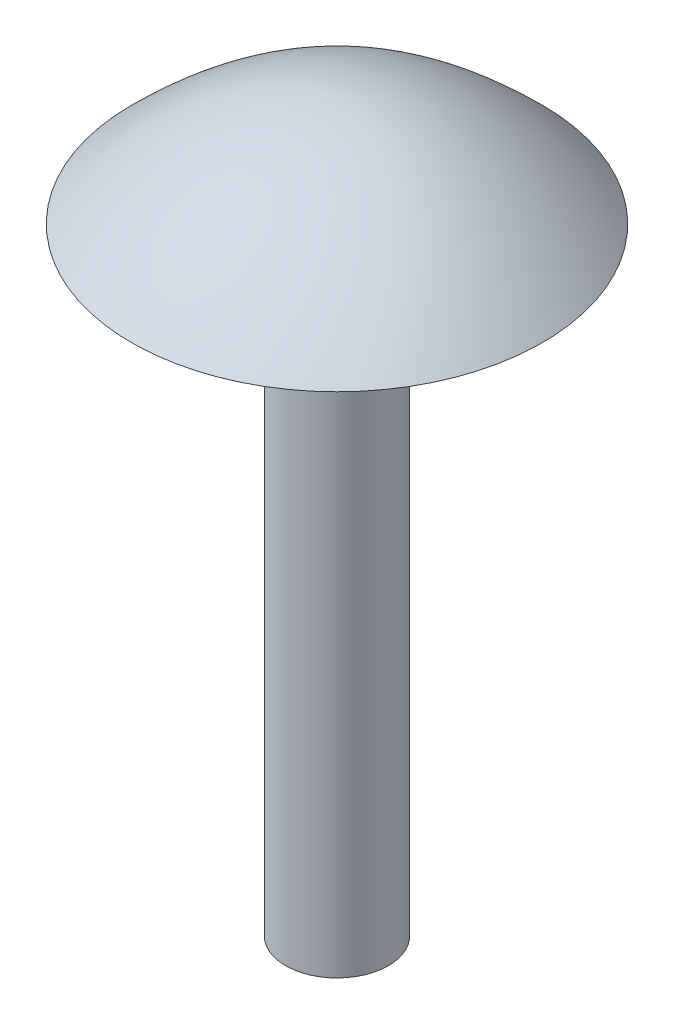
SolidWorks part; units mm, degrees
ref_plane "Front Plane" through (0, 0, 0) normal (0, 0, 1) x (1, 0, 0)
ref_plane "Top Plane" through (0, 0, 0) normal (0, 1, 0) x (1, 0, 0)
ref_plane "Right Plane" through (0, 0, 0) normal (1, 0, 0) x (0, 0, -1)
sketch "Sketch1" plane through (0, 0, 0) normal (0, 0, 1) x (1, 0, 0)
  line L0 (0, 0) -> (0, 6)
  line L1 (0, 0) -> (0.5, 0)
  line L2 (0, 6) -> (-1.5, 6)
  line L3 (0.5, -1.4044) -> (0.5, 9.5529) construction
  line L4 (0.5, 0) -> (0.5, 7)
  spline S0 degree 2 poles (-1.5, 6) (-0.5, 7) (0.5, 7) knots 0 0 0 0.5 0.5 0.5
  point P8 (0, 0)
  point P9 (0, 0)
  point P10 (0, 0)
  point P11 (0, 0)
  point P12 (0, 0)
revolve "Revolve1" add sketch "Sketch1" angle 360 about L3
